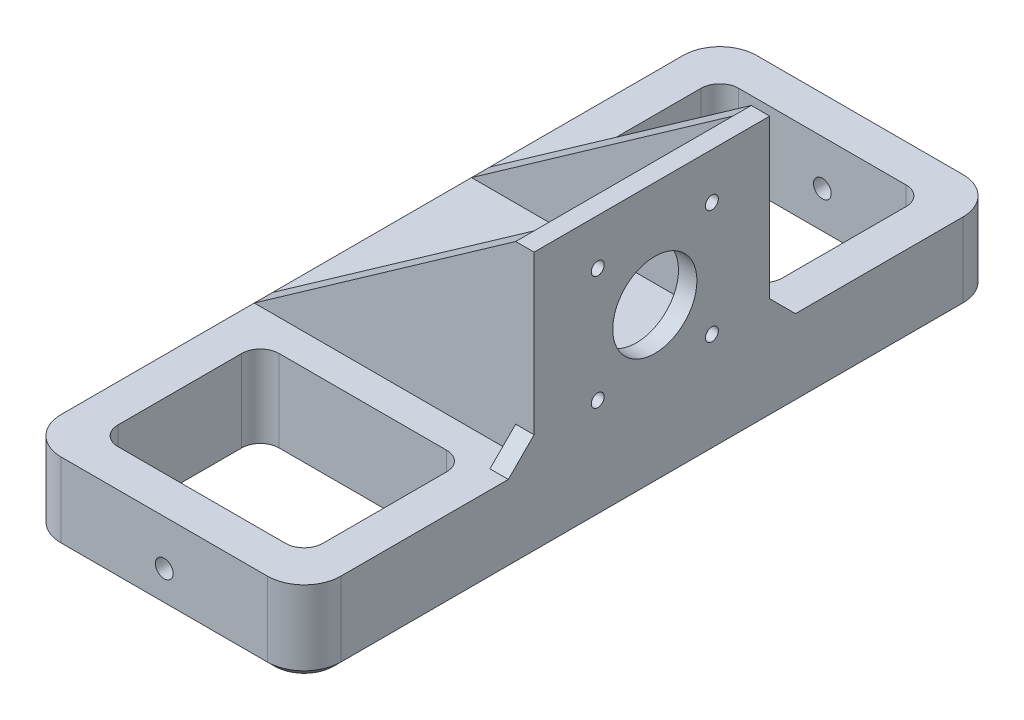
SolidWorks part; units mm, degrees
material "PF"
ref_plane "Front Plane" through (0, 0, 0) normal (0, 0, 1) x (1, 0, 0)
ref_plane "Top Plane" through (0, 0, 0) normal (0, 1, 0) x (1, 0, 0)
ref_plane "Right Plane" through (0, 0, 0) normal (1, 0, 0) x (0, 0, -1)
sketch "Sketch1" plane through (0, 0, 0) normal (1, 0, 0) x (0, 0, -1)
  line L0 (-0.7938, -17.78) -> (-0.7938, 4.445) construction
  line L1 (-95.25, 4.445) -> (93.6625, 4.445)
  line L2 (-95.25, 4.445) -> (-95.25, -17.78)
  line L3 (-95.25, -17.78) -> (93.6625, -17.78)
  line L4 (93.6625, 4.445) -> (93.6625, -17.78)
  line L5 (-95.25, 4.445) -> (93.6625, -17.78) construction
  line L6 (-95.25, -17.78) -> (93.6625, 4.445) construction
  point P0 (0, 0)
  dimension "D1" = 22.225
  dimension "D2" = 94.4562
extrude "Boss-Extrude1" add sketch "Sketch1" along normal blind 64 and the other way blind 12
sketch "Sketch3" plane through (64, 8.8661, 9.6636) normal (1, 0, 0) x (0, 0, -1)
  line L0 (38.8698, 45.5501) -> (-21.1302, 45.5501)
  line L1 (38.8698, 45.5501) -> (38.8698, -4.4499)
  line L2 (-21.1302, 45.5501) -> (-21.1302, -4.4499)
  line L3 (38.8698, -4.4499) -> (-21.1302, -4.4499)
  line L4 (38.8698, 45.5501) -> (-21.1302, -4.4499) construction
  line L5 (-21.1302, 45.5501) -> (38.8698, -4.4499) construction
  line L8 (-85.5864, -26.6461) -> (103.3261, -26.6461) construction
  point P1 (8.8698, 20.5501)
  point P8 (8.8698, -26.6461)
  dimension "D1" = 60
  dimension "D2" = 50
  dimension "D3" = 64.4563
  dimension "D4" = 64.4563
extrude "Boss-Extrude2" add sketch "Sketch3" against normal blind 5
sketch "Sketch4" plane through (64, 0, 0) normal (1, 0, 0) x (0, 0, -1)
  line L0 (0, 49.4107) -> (0, -12.8565) construction
  line L1 (-30.7937, 4.445) -> (29.2063, 4.445) construction
  circle A0 centre (0, 25.6032) radius 11.43
  circle A1 centre (-15.5, 41.945) radius 1.75
  circle A2 centre (15.5, 41.945) radius 1.75
  circle A3 centre (-15.5, 10.945) radius 1.75
  circle A4 centre (15.5, 10.945) radius 1.75
  dimension "D2" = 3.5
  dimension "D5" = 6.5
  dimension "D7" = 22.86
  dimension "D8" = 3.5
  dimension "D9" = 3.5
  dimension "D1" = 15.5
  dimension "D4" = 31
  dimension "D6" = 31
  dimension "D10" = 21.1582
  dimension "D3" = 2
extrude "Cut-Extrude1" cut sketch "Sketch4" against normal blind 5
fillet "Fillet2" radius 10 1 edges at (-12, -6.6675, 95.25)
fillet "Fillet3" radius 10 1 edges at (64, -6.6675, 95.25)
fillet "Fillet6" radius 10 1 edges at (-12, -6.6675, -93.6625)
fillet "Fillet8" radius 10 1 edges at (64, -6.6675, -93.6625)
sketch "Sketch18" plane through (0, 4.445, 0) normal (0, 1, 0) x (1, 0, 0)
  line L0 (64, -85.25) -> (64, -30.7937) construction
  line L1 (59, -30.7937) -> (64, -30.7937)
  line L2 (59, -30.7937) -> (59, -32.7937)
  line L3 (59, -32.7937) -> (64, -32.7937)
  line L4 (64, -30.7937) -> (64, -32.7937)
  dimension "D1" = 2
extrude "Boss-Extrude4" add sketch "Sketch18" along normal up to vertex (49.9712 mm away) up to point (64, 54.4162, 30.7938)
sketch "Sketch19" plane through (0, 4.445, 0) normal (0, 1, 0) x (1, 0, 0)
  line L0 (64, 29.2062) -> (64, 83.6625) construction
  line L1 (59, 29.2063) -> (64, 29.2063)
  line L2 (59, 29.2063) -> (59, 31.2062)
  line L3 (59, 31.2062) -> (64, 31.2062)
  line L4 (64, 29.2063) -> (64, 31.2062)
  dimension "D1" = 2
extrude "Boss-Extrude5" add sketch "Sketch19" along normal up to vertex (49.9712 mm away)
sketch "Sketch26" plane through (0, 0, 95.25) normal (0, 0, 1) x (1, 0, 0)
  line L0 (26, 2.22) -> (26, -17.78) construction
  line L2 (-2, -17.78) -> (54, -17.78) construction
  circle A0 centre (26, -7.78) radius 2.413
  dimension "D1" = 4.826
  dimension "D2" = 10
extrude "Cut-Extrude3" cut sketch "Sketch26" against normal blind 31.496
chamfer "Chamfer1" distance 7 angle 45 2 edges at (61.5, 4.445, -31.2062) (61.5, 4.445, 32.7937)
chamfer "Chamfer2" distance 2 angle 45 8 edges at (64, -17.78, 0.7938) (-12, -17.78, 0.7938) (61.0711, -17.78, 92.3211) (-9.0711, -17.78, 92.3211) (61.0711, -17.78, -90.7336) (-9.0711, -17.78, -90.7336) (26, -17.78, 95.25) (26, -17.78, -93.6625)
sketch "Sketch20" plane through (0, 0, -31.2062) normal (0, 0, -1) x (-1, 0, 0)
  line L0 (-59, 54.4162) -> (12, 4.445)
  line L1 (12, 4.445) -> (-59, 4.445)
  line L2 (-54, 4.445) -> (-64, 4.445) construction
  line L3 (-59, 4.445) -> (-59, 54.4162)
extrude "Boss-Extrude6" add sketch "Sketch20" against normal blind 5
sketch "Sketch21" plane through (0, 0, 32.7937) normal (0, 0, 1) x (1, 0, 0)
  line L0 (59, 54.4162) -> (-12, 4.445)
  line L1 (-12, 4.445) -> (59, 4.445)
  line L2 (59, 4.445) -> (59, 54.4162)
extrude "Boss-Extrude7" add sketch "Sketch21" against normal blind 5
sketch "Sketch23" plane through (0, 4.445, 0) normal (0, 1, 0) x (1, 0, 0)
  line L0 (26, -95.25) -> (26, -31.1339) construction
  line L1 (-2, -95.25) -> (54, -95.25) construction
  line L2 (-12, -85.25) -> (-12, -32.7937) construction
  line L3 (48.76, -41.2939) -> (3.24, -41.2939)
  line L4 (53.84, -46.3739) -> (53.84, -80.01)
  line L5 (48.76, -85.09) -> (3.24, -85.09)
  line L6 (-1.84, -46.3739) -> (-1.84, -80.01)
  line L7 (53.84, -41.2939) -> (-1.84, -85.09) construction
  line L8 (53.84, -85.09) -> (-1.84, -41.2939) construction
  line L9 (59, -0.7937) -> (-6.3077, -0.7938) construction
  line L10 (59, -27.7937) -> (59, 26.2062) construction
  line L11 (48.76, 83.5025) -> (3.24, 83.5025)
  line L12 (-1.84, 44.7864) -> (-1.84, 78.4225)
  line L13 (48.76, 39.7064) -> (3.24, 39.7064)
  line L14 (53.84, 44.7864) -> (53.84, 78.4225)
  arc A0 (53.84, -46.3739) -> (48.76, -41.2939) centre (48.76, -46.3739) ccw
  arc A1 (-1.84, -80.01) -> (3.24, -85.09) centre (3.24, -80.01) ccw
  arc A2 (3.24, -41.2939) -> (-1.84, -46.3739) centre (3.24, -46.3739) ccw
  arc A3 (48.76, -85.09) -> (53.84, -80.01) centre (48.76, -80.01) ccw
  arc A4 (-1.84, 78.4225) -> (3.24, 83.5025) centre (3.24, 78.4225) cw
  arc A5 (3.24, 39.7064) -> (-1.84, 44.7864) centre (3.24, 44.7864) cw
  arc A6 (53.84, 44.7864) -> (48.76, 39.7064) centre (48.76, 44.7864) cw
  arc A7 (48.76, 83.5025) -> (53.84, 78.4225) centre (48.76, 78.4225) cw
  point P4 (26, -63.192)
  dimension "D3" = 5.08
  dimension "D1" = 10.16
  dimension "D2" = 10.16
extrude "Cut-Extrude2" cut sketch "Sketch23" against normal through all
sketch "Sketch27" plane through (0, 0, -93.6625) normal (0, 0, 1) x (1, 0, 0)
  line L0 (26, 2.22) -> (26, -17.78) construction
  circle A0 centre (26, -7.78) radius 2.413
  dimension "D1" = 4.826
extrude "Cut-Extrude4" cut sketch "Sketch27" along normal blind 16.51
